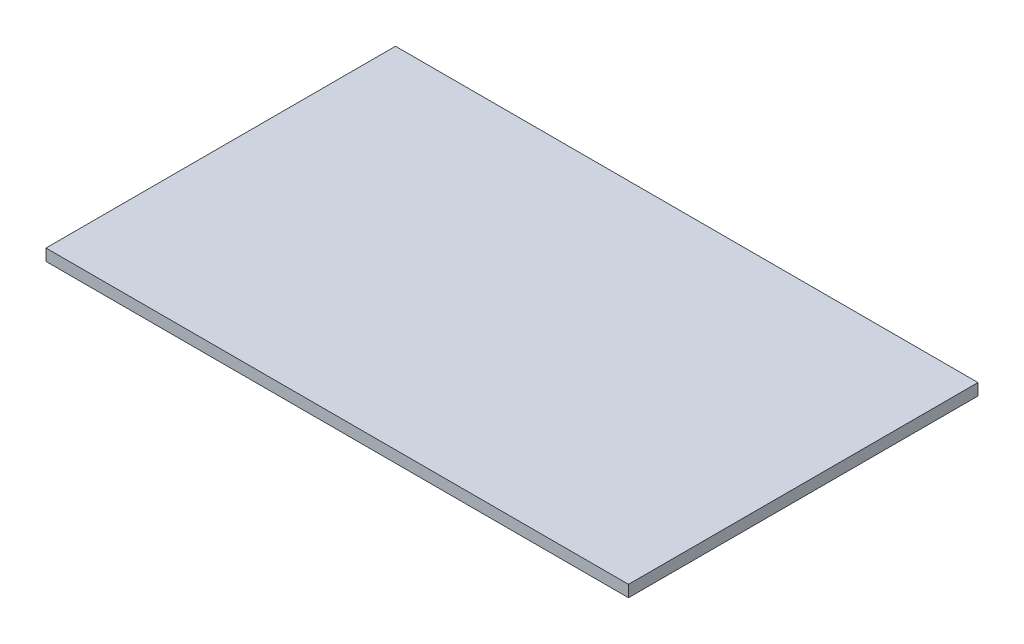
SolidWorks part; units mm, degrees
ref_plane "Alzado" through (0, 0, 0) normal (0, 0, 1) x (1, 0, 0)
ref_plane "Planta" through (0, 0, 0) normal (0, 1, 0) x (1, 0, 0)
ref_plane "Vista lateral" through (0, 0, 0) normal (1, 0, 0) x (0, 0, -1)
sketch "Croquis1" plane through (0, 0, 0) normal (0, 1, 0) x (1, 0, 0)
  line L1 (250, -150) -> (-250, -150)
  line L2 (250, -150) -> (250, 150)
  line L3 (250, 150) -> (-250, 150)
  line L4 (-250, -150) -> (-250, 150)
  line L5 (250, -150) -> (-250, 150) construction
  line L6 (250, 150) -> (-250, -150) construction
  point P0 (0, 0)
  dimension "D1" = 500
  dimension "D2" = 300
extrude "Saliente-Extruir1" add sketch "Croquis1" along normal blind 10
